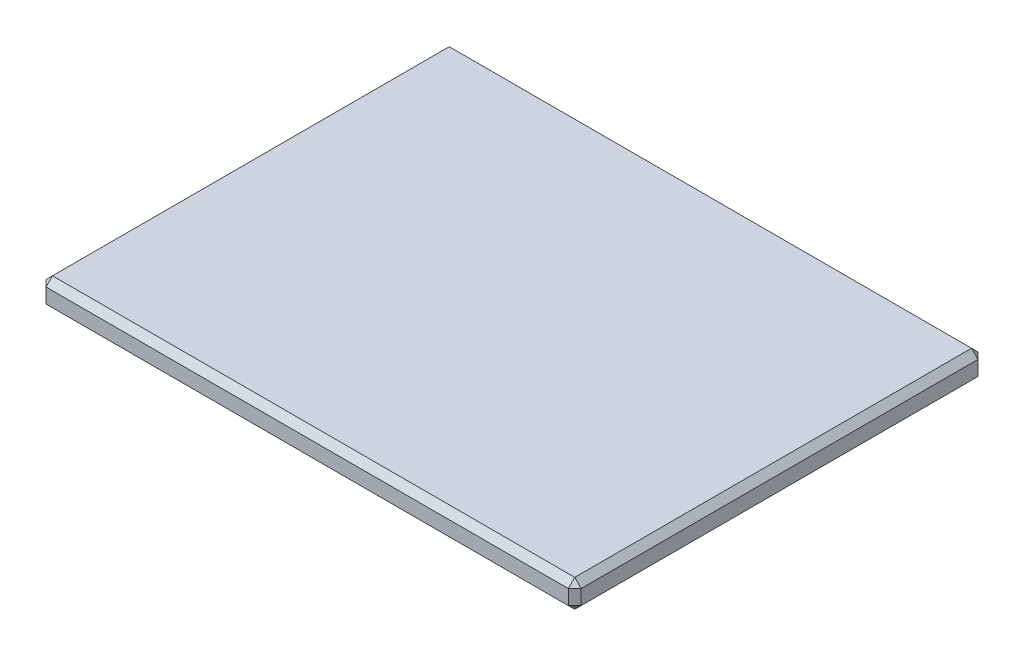
SolidWorks part; units mm, degrees
ref_plane "Front Plane" through (0, 0, 0) normal (0, 0, 1) x (1, 0, 0)
ref_plane "Top Plane" through (0, 0, 0) normal (0, 1, 0) x (1, 0, 0)
ref_plane "Right Plane" through (0, 0, 0) normal (1, 0, 0) x (0, 0, -1)
sketch "Sketch1" plane through (0, 0, 0) normal (0, 1, 0) x (1, 0, 0)
  line L1 (-36.83, -28.194) -> (36.83, -28.194)
  line L2 (-36.83, -28.194) -> (-36.83, 28.194)
  line L3 (-36.83, 28.194) -> (36.83, 28.194)
  line L4 (36.83, -28.194) -> (36.83, 28.194)
  line L5 (-36.83, -28.194) -> (36.83, 28.194) construction
  line L6 (-36.83, 28.194) -> (36.83, -28.194) construction
  point P0 (0, 0)
  dimension "D1" = 73.66
  dimension "D2" = 56.388
extrude "Boss-Extrude1" add sketch "Sketch1" against normal blind 3.81
chamfer "Chamfer1" distance 0.889 angle 45 12 edges at (0, -3.81, -28.194) (-36.83, -3.81, 0) (-36.83, -1.905, -28.194) (36.83, -1.905, -28.194) (36.83, -3.81, 0) (-36.83, 0, 0) (0, 0, -28.194) (36.83, 0, 0) (36.83, -1.905, 28.194) (0, -3.81, 28.194) (-36.83, -1.905, 28.194) (0, 0, 28.194)
